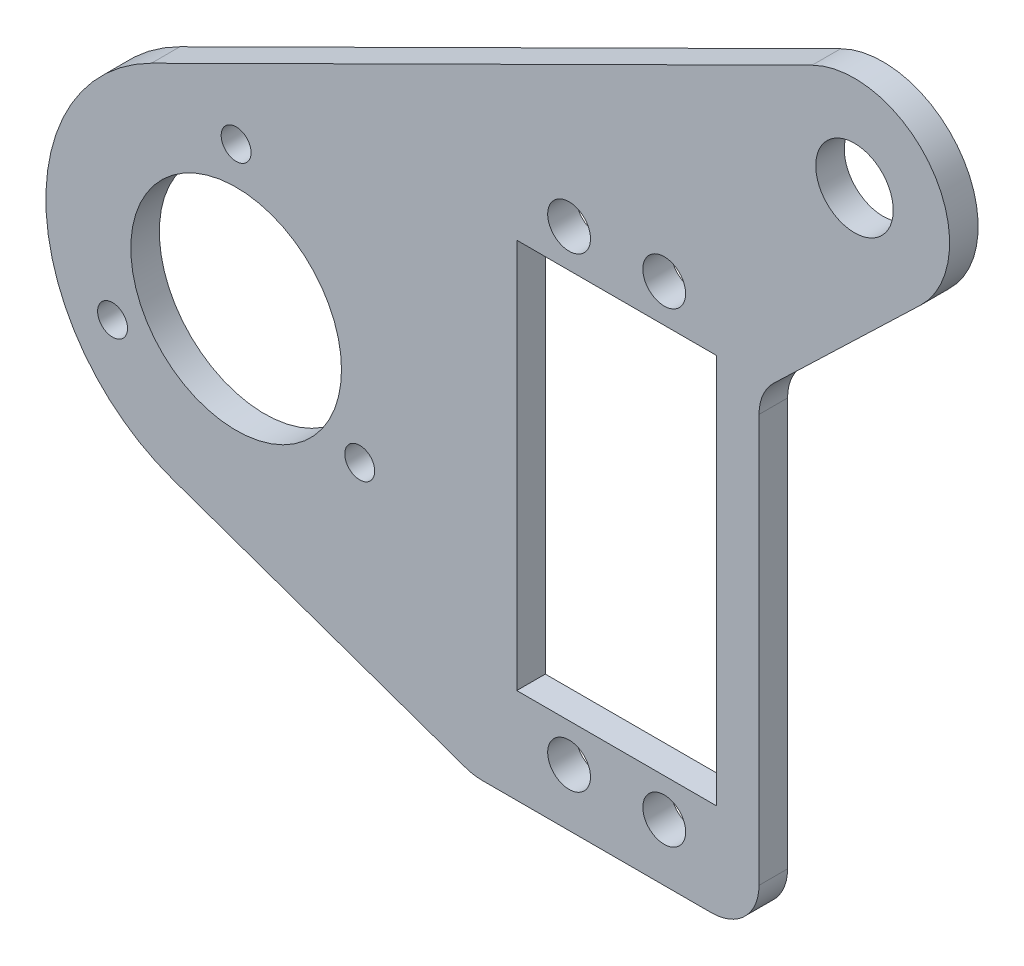
SolidWorks part; units mm, degrees
material "Acrylic (Medium-high impact)"
ref_plane "Front Plane" through (0, 0, 0) normal (0, 0, 1) x (1, 0, 0)
ref_plane "Top Plane" through (0, 0, 0) normal (0, 1, 0) x (1, 0, 0)
ref_plane "Right Plane" through (0, 0, 0) normal (1, 0, 0) x (0, 0, -1)
sketch "Sketch1" plane through (0, 0, 0) normal (0, 0, 1) x (1, 0, 0)
  line L0 (24.965, -30) -> (-6.6456, -18.8636)
  line L3 (24.965, -30) -> (54.965, -30)
  line L6 (60.5465, 52.4536) -> (-8.9071, 17.9071)
  line L8 (54.965, -30) -> (54.965, 20)
  line L9 (54.965, 20) -> (71.9262, 36.287)
  arc A0 (20, 0) -> (-8.9071, 17.9071) centre (0, 0) ccw construction
  arc A1 (-6.6456, -18.8636) -> (20, 0) centre (0, 0) ccw construction
  circle A2 centre (0, 0) radius 11.075
  arc A3 (71.9262, 36.287) -> (60.5465, 52.4536) centre (65, 43.5) ccw
  circle A4 centre (65, 43.5) radius 4.075
  arc A5 (60.5465, 52.4536) -> (71.9262, 36.287) centre (65, 43.5) ccw construction
  circle A6 centre (0, 0) radius 20 construction
  arc A7 (-8.9071, 17.9071) -> (-6.6456, -18.8636) centre (0, 0) ccw
  arc A8 (71.9262, 36.287) -> (60.5465, 52.4536) centre (65, 43.5) ccw construction
  arc A9 (60.5465, 52.4536) -> (71.9262, 36.287) centre (65, 43.5) ccw construction
  dimension "D1" = 40
  dimension "D6" = 22.15
  dimension "D7" = 20
  dimension "D10" = 8.15
  dimension "D2" = 30
  dimension "D5" = 30
  dimension "D8" = 43.5
  dimension "D9" = 65
  dimension "D3" = 31.6106
  dimension "D4" = 50
extrude "Boss-Extrude1" add sketch "Sketch1" along normal blind 3
sketch "Sketch2" plane through (0, 0, 0) normal (0, 0, 1) x (1, 0, 0)
  circle A0 centre (0, 0) radius 15 construction
  circle A1 centre (0, 15) radius 1.575
  circle A2 centre (12.9904, -7.5) radius 1.575
  circle A3 centre (-12.9904, -7.5) radius 1.575
  point P12 (0, 0)
  dimension "D1" = 30
  dimension "D2" = 3.15
  dimension "D3" = 3
extrude "Cut-Extrude1" cut sketch "Sketch2" along normal through all both and the other way through all
sketch "Sketch6" plane through (0, 0, 0) normal (0, 0, 1) x (1, 0, 0)
  line L0 (40, -24) -> (40, 25) construction
  line L1 (35, -24) -> (35, 25) construction
  line L2 (35, -24) -> (45, -24) construction
  line L3 (35, 25) -> (45, 25) construction
  line L4 (45, -24) -> (45, 25) construction
  circle A0 centre (35, -24) radius 2.25
  circle A1 centre (35, 25) radius 2.25
  circle A2 centre (45, 25) radius 2.25
  circle A3 centre (45, -24) radius 2.25
  dimension "D5" = 4.5
  dimension "D1" = 49
  dimension "D2" = 10
  dimension "D3" = 25
  dimension "D4" = 40
extrude "Cut-Extrude5" cut sketch "Sketch6" along normal through all both and the other way through all contours A2 | A1 | A0 | A3
fillet "Fillet2" radius 5 3 edges at (24.965, -30, 1.5) (54.965, 20, 1.5) (54.965, -30, 1.5)
sketch "Sketch7" plane through (0, 0, 0) normal (0, 0, 1) x (1, 0, 0)
  line L0 (35, 25) -> (45, 25) construction
  line L1 (29.5, -20) -> (50.5, -20)
  line L2 (29.5, -20) -> (29.5, 21)
  line L3 (29.5, 21) -> (50.5, 21)
  line L4 (50.5, -20) -> (50.5, 21)
  line L5 (40, 21) -> (40, -20) construction
  line L6 (29.5, 0.5) -> (50.5, 0.5) construction
  line L7 (40, 25) -> (40, -24) construction
  line L8 (45, -24) -> (35, -24) construction
  point P0 (40, 0.5)
  point P7 (40, 25)
  point P18 (40, 0.5)
  dimension "D1" = 41
  dimension "D2" = 21
extrude "Cut-Extrude6" cut sketch "Sketch7" along normal through all both and the other way through all
sketch "Sketch8" [suppressed] plane through (0, 0, 0) normal (0, 0, 1) x (1, 0, 0)
  line L0 (45, -24) -> (35, -24) construction
  line L1 (40, -24) -> (40, -9.5) construction
  line L2 (40, -9.5) -> (40, 1.5) construction
  line L3 (40, -9.5) -> (42.6047, 5.2721) construction
  circle A0 centre (40, -9.5) radius 11
  circle A1 centre (42.6047, 5.2721) radius 1.5
  circle A2 centre (51.4907, -19.1418) radius 1.5
  circle A3 centre (25.9046, -14.6303) radius 1.5
  dimension "D1" = 22
  dimension "D3" = 15
  dimension "D4" = 3
  dimension "D2" = 14.5
  dimension "D5" = 10
  dimension "D6" = 3
extrude "Cut-Extrude7" [suppressed] cut sketch "Sketch8" along normal through all both and the other way through all
sketch "Sketch3" [suppressed] plane through (0, 0, 0) normal (0, 0, 1) x (1, 0, 0)
  circle A0 centre (65, 37.5) radius 15 construction
  circle A1 centre (65, 52.5) radius 1.5
  circle A2 centre (77.9904, 30) radius 1.5
  circle A3 centre (52.0096, 30) radius 1.5
  dimension "D1" = 3
  dimension "D2" = 30
  dimension "D3" = 3
extrude "Cut-Extrude2" [suppressed] cut sketch "Sketch3" along normal through all both and the other way through all
equation "\"Tolerance\"= 0.15"
equation "\"D6@Sketch1\"=22+\"Tolerance\""
equation "\"D10@Sketch1\"=8+\"Tolerance\""
equation "\"D2@Sketch2\"=3+\"Tolerance\""
